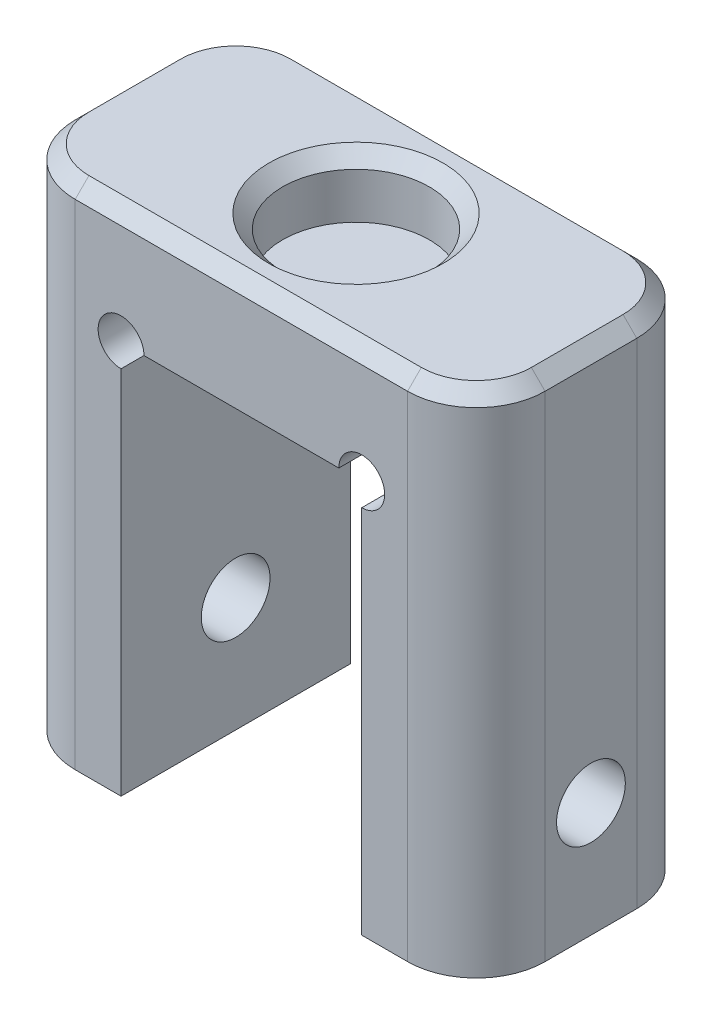
SolidWorks part; units mm, degrees
material "ﾎﾟﾘｴｽﾃﾙ樹脂"
ref_plane "正面" through (0, 0, 0) normal (0, 0, 1) x (1, 0, 0)
ref_plane "平面" through (0, 0, 0) normal (0, 1, 0) x (1, 0, 0)
ref_plane "右側面" through (0, 0, 0) normal (1, 0, 0) x (0, 0, -1)
sketch "ｽｹｯﾁ1" plane through (0, 0, 0) normal (0, 0, 1) x (1, 0, 0)
  line L0 (0, 11.075) -> (0, -11.075) construction
  line L1 (-10.25, -11.075) -> (10.25, -11.075)
  line L2 (-10.25, -11.075) -> (-10.25, 11.075)
  line L3 (-10.25, 11.075) -> (10.25, 11.075)
  line L4 (10.25, -11.075) -> (10.25, 11.075)
  line L5 (-10.25, -11.075) -> (10.25, 11.075) construction
  line L6 (-10.25, 11.075) -> (10.25, -11.075) construction
  line L8 (-5.25, 6.075) -> (5.25, 6.075)
  line L9 (-5.25, 6.075) -> (-5.25, -11.075)
  line L10 (-5.25, -11.075) -> (5.25, -11.075)
  line L11 (5.25, 6.075) -> (5.25, -11.075)
  line L12 (-5.25, 6.075) -> (5.25, -11.075) construction
  line L13 (-5.25, -11.075) -> (5.25, 6.075) construction
  point P0 (0, 0)
  point P7 (0, -2.5)
  dimension "D1" = 17.15
  dimension "D2" = 5
  dimension "D3" = 5
  dimension "D4" = 10.5
extrude "ﾎﾞｽ - 押し出し1" add sketch "ｽｹｯﾁ1" along normal blind 10 contours L8 L11 L1 L4 L3 L2 L9
sketch "ｽｹｯﾁ2" plane through (0, 11.075, 0) normal (0, 1, 0) x (1, 0, 0)
  line L0 (0, 0) -> (0, -10) construction
  line L1 (-10.25, -10) -> (10.25, -10) construction
  circle A0 centre (0, -5) radius 3.2
  dimension "D1" = 6.4
extrude "ｶｯﾄ - 押し出し1" cut sketch "ｽｹｯﾁ2" against normal blind 2.6
sketch "ｽｹｯﾁ3" plane through (10.25, 0, 0) normal (1, 0, 0) x (0, 0, -1)
  line L0 (-5, 11.075) -> (-5, -11.075) construction
  line L1 (-10, 11.075) -> (0, 11.075) construction
  line L2 (-10, -11.075) -> (0, -11.075) construction
  circle A0 centre (-5, -6.075) radius 1.5
  dimension "D1" = 5
  dimension "D2" = 3
extrude "ｶｯﾄ - 押し出し2" cut sketch "ｽｹｯﾁ3" against normal through all
fillet "ﾌｨﾚｯﾄ1" radius 3 4 edges at (-10.25, 0, 10) (-10.25, 0, 0) (10.25, 0, 0) (10.25, 0, 10)
chamfer "面取り1" distance 0.6 angle 45 9 edges at (-9.3713, 11.075, 0.8787) (0, 11.075, 0) (9.3713, 11.075, 0.8787) (10.25, 11.075, 5) (9.3713, 11.075, 9.1213) (0, 11.075, 10) (-9.3713, 11.075, 9.1213) (-10.25, 11.075, 5) (-3.2, 11.075, 5)
sketch "ｽｹｯﾁ4" plane through (0, 0, 10) normal (0, 0, 1) x (1, 0, 0)
  circle A0 centre (5.25, 6.075) radius 1
  circle A1 centre (-5.25, 6.075) radius 1
  dimension "D1" = 2
extrude "ｶｯﾄ - 押し出し3" cut sketch "ｽｹｯﾁ4" against normal through all
